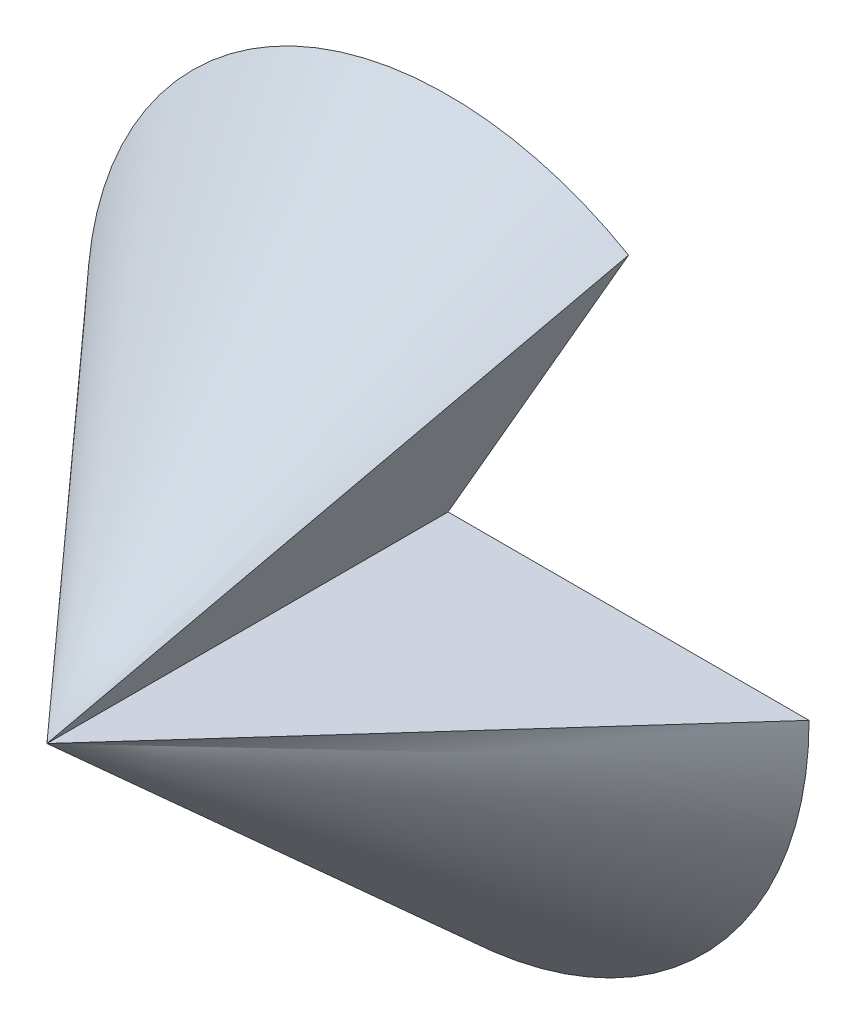
SolidWorks part; units mm, degrees
ref_plane "Front Plane" through (0, 0, 0) normal (0, 0, 1) x (1, 0, 0)
ref_plane "Top Plane" through (0, 0, 0) normal (0, 1, 0) x (1, 0, 0)
ref_plane "Right Plane" through (0, 0, 0) normal (1, 0, 0) x (0, 0, -1)
sketch "Sketch1" plane through (0, 0, 0) normal (0, 0, 1) x (1, 0, 0)
  line L0 (0, 0) -> (45, 0)
  line L1 (0, 0) -> (22.5, -38.9711)
  circle A0 centre (0, 0) radius 45
  dimension "D1" = 60
sketch "Sketch3" plane through (0, 0, 0) normal (0, 1, 0) x (1, 0, 0)
  line L0 (0, 0) -> (45, 0)
  line L1 (0, 0) -> (45, 0) construction
  line L2 (-49.5, 0) -> (49.5, 0) construction
  line L3 (45, 0) -> (0, -50)
  line L4 (0, -49.5) -> (0, 49.5) construction
  line L5 (0, -50) -> (0, 0)
  dimension "D1" = 50
revolve "Revolve1" add sketch "Sketch3" angle 300 about L5
